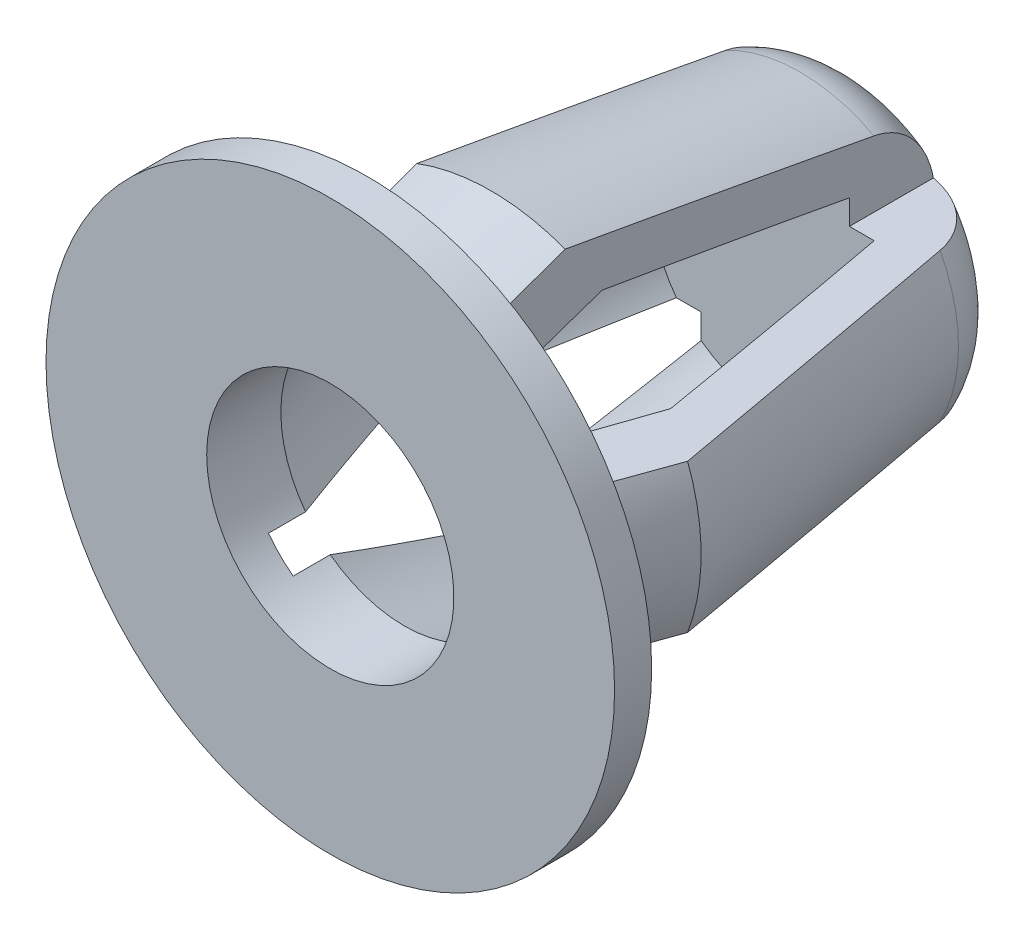
SolidWorks part; units mm, degrees
ref_plane "正面" through (0, 0, 0) normal (0, 0, 1) x (1, 0, 0)
ref_plane "平面" through (0, 0, 0) normal (0, 1, 0) x (1, 0, 0)
ref_plane "右側面" through (0, 0, 0) normal (1, 0, 0) x (0, 0, -1)
sketch "ｽｹｯﾁ1" plane through (0, 0, 0) normal (1, 0, 0) x (0, 0, -1)
  line L0 (0, 0) -> (-92.9851, 0) construction
  line L1 (0, 7.5) -> (2, 7.5)
  line L2 (2, 7.5) -> (5, 8.5)
  line L3 (5, 8.5) -> (20, 6)
  line L4 (20, 6) -> (20, 0)
  line L5 (20, 0) -> (16.5, 0)
  line L6 (16.5, 0) -> (16.5, 5)
  line L7 (1.5, 5) -> (-1.5, 5)
  line L8 (-1.5, 5) -> (-1.5, 11.5)
  line L9 (-1.5, 11.5) -> (0, 11.5)
  line L10 (0, 11.5) -> (0, 7.5)
  line L11 (1.5, 5) -> (6.5, 6.5)
  line L12 (6.5, 6.5) -> (16.5, 5)
  dimension "D1" = 15
  dimension "D2" = 23
  dimension "D3" = 1.5
  dimension "D4" = 10
  dimension "D5" = 18
  dimension "D6" = 20
  dimension "D7" = 12
  dimension "D8" = 17
  dimension "D9" = 2
  dimension "D10" = 5
  dimension "D11" = 3
  dimension "D12" = 5
  dimension "D13" = 13
  dimension "D14" = 10
revolve "回転1" add sketch "ｽｹｯﾁ1" angle 360 about L0
fillet "ﾌｨﾚｯﾄ1" radius 3 1 edges at (-6, 0, -20)
sketch "ｽｹｯﾁ2" plane through (0, 0, -20) normal (0, 0, -1) x (-1, 0, 0)
  line L1 (3, 3) -> (13.6436, 3)
  line L2 (3, 3) -> (3, 12.0976)
  line L3 (3, 12.0976) -> (13.6436, 12.0976)
  line L4 (13.6436, 3) -> (13.6436, 12.0976)
  circle A0 centre (0, 0) radius 3 construction
  dimension "D1" = 6
  dimension "D2" = 3
  dimension "D3" = 3
  dimension "D4" = 3
extrude "ｶｯﾄ - 押し出し1" cut sketch "ｽｹｯﾁ2" against normal up to surface (20 mm away) up to face at (-11.5, 0, 0)
pattern_circular "円形ﾊﾟﾀｰﾝ1" count 4 over 360 about axis through (0, 0, 0) along (0, 0, 1) of "ｶｯﾄ - 押し出し1"
